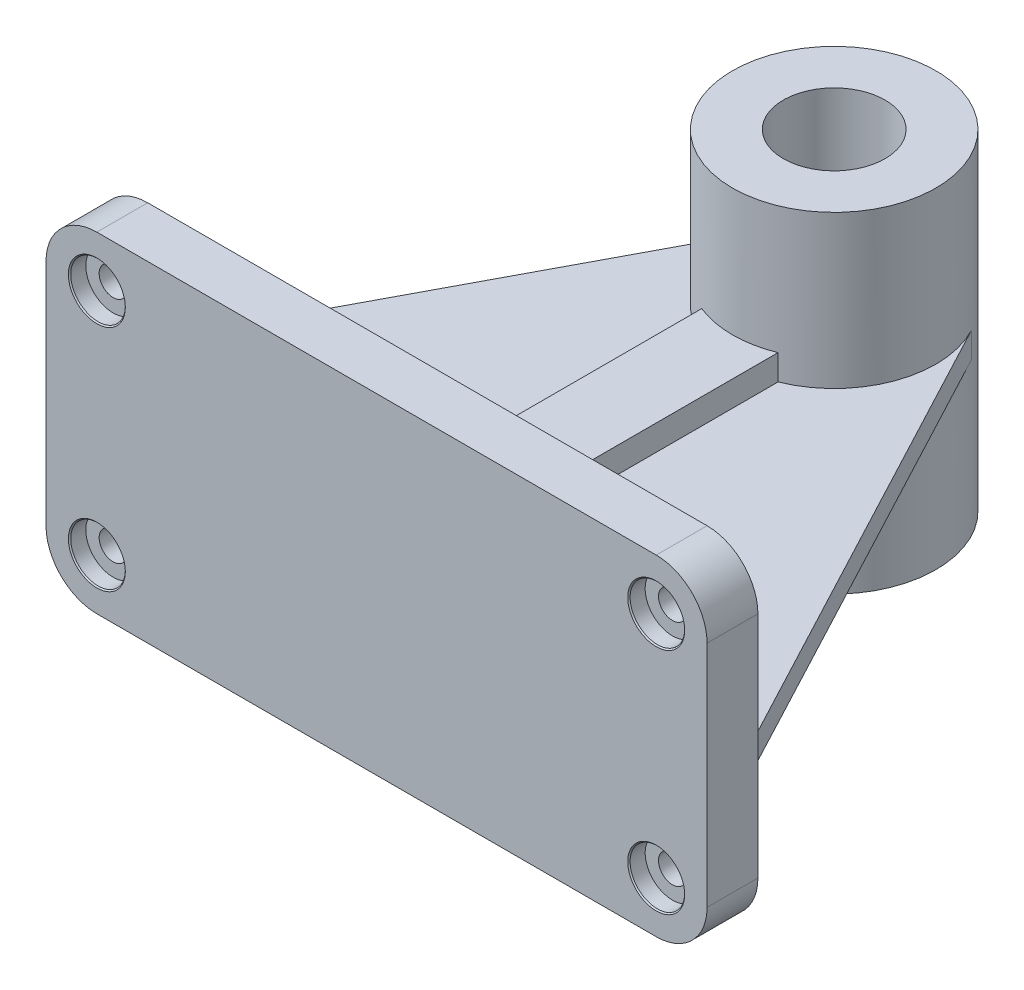
SolidWorks part; units mm, degrees
ref_plane "前视基准面" through (0, 0, 0) normal (0, 0, 1) x (1, 0, 0)
ref_plane "上视基准面" through (0, 0, 0) normal (0, 1, 0) x (1, 0, 0)
ref_plane "右视基准面" through (0, 0, 0) normal (1, 0, 0) x (0, 0, -1)
sketch "草图1" plane through (0, 0, 0) normal (0, 0, 1) x (1, 0, 0)
  line L0 (-164.2424, 0) -> (206.0606, 0) construction
  line L1 (-130, 65) -> (130, 65)
  line L2 (-130, 65) -> (-130, -65)
  line L3 (-130, -65) -> (130, -65)
  line L4 (130, 65) -> (130, -65)
  line L5 (0, 96.0606) -> (0, -170) construction
  point P4 (-164.2424, 3.0303)
  point P8 (0, 65)
  point P11 (-130, 0)
  dimension "D1" = 260
  dimension "D2" = 130
extrude "凸台-拉伸1" add sketch "草图1" along normal blind 20
hole_wizard "M10 六角头螺栓的柱形沉头孔1" positions "3D草图1" profile "草图3" counterbore size "M10" standard "ISO"
sketch3d "3D草图1"
  line L0 (130, 65, 20) -> (-130, 65, 20) construction
  line L1 (-130, 65, 20) -> (-130, -65, 20) construction
  point P0 (-110, 45, 20)
  dimension "D1" = 20
  dimension "D2" = 20
sketch "草图3" plane through (-110, 45, 20) normal (1, 0, 0) x (0, -1, 0)
  line L0 (0, 0) -> (0, 30.8047)
  line L1 (0, 30.8047) -> (5.5, 27.5)
  line L2 (5.5, 27.5) -> (5.5, 6.4)
  line L3 (5.5, 6.4) -> (10.7375, 6.4)
  line L5 (10.7375, 6.4) -> (10.7375, 0.4625)
  line L6 (10.7375, 0.4625) -> (11.2, 0)
  line L7 (11.2, 0) -> (0, 0)
  line L8 (-10.7375, 0.4625) -> (-11.2, 0) construction
  line L10 (0, 30.8047) -> (-5.5, 27.5) construction
  line L11 (0, -6.35) -> (0, 107.95) construction
  dimension "孔直径" = 11
  dimension "孔深度" = 27.5
  dimension "锥形沉头孔直径" = 21.475
  dimension "锥形沉头孔深度" = 6.4
  dimension "近端锥形沉头孔直径" = 22.4
  dimension "近端锥形沉头孔角度" = 90
  dimension "导头角度" = 118
mirror "镜向1" about plane through (0, 0, 0) normal (0, 1, 0) of "M10 六角头螺栓的柱形沉头孔1"
mirror "镜向2" about plane through (0, 0, 0) normal (1, 0, 0) of "镜向1", "M10 六角头螺栓的柱形沉头孔1"
sketch "草图4" plane through (0, 0, 0) normal (0, 1, 0) x (1, 0, 0)
  line L0 (130, 0) -> (-130, 0) construction
  circle A0 centre (0, 160) radius 40
  dimension "D1" = 80
  dimension "D2" = 160
extrude "凸台-拉伸2" add sketch "草图4" along normal mid plane 130 separate body
sketch "草图5" plane through (0, 0, 0) normal (0, 1, 0) x (1, 0, 0)
  line L0 (-15, 122.919) -> (-15, 0)
  line L1 (130, 0) -> (-130, 0) construction
  line L2 (0, 194.1484) -> (0, -59.9284) construction
  line L3 (15, 122.919) -> (15, 0)
  line L6 (-15, 0) -> (15, 0)
  circle A1 centre (0, 160) radius 40
  arc A2 (-15, 122.919) -> (15, 122.919) centre (0, 160) ccw
  dimension "D1" = 0
  dimension "D2" = 15
extrude "凸台-拉伸3" add sketch "草图5" along normal mid plane 30
sketch "草图6" plane through (0, 0, 0) normal (0, 1, 0) x (1, 0, 0)
  line L1 (130, 0) -> (35.3487, 178.7208)
  circle A0 centre (0, 160) radius 40 construction
rib "筋4" sketch "草图6" sketch "草图6" thickness 10 extrusion direction parallel to sketch draft on no parameters "D1"=10
mirror "镜向3" about plane through (0, 0, 0) normal (1, 0, 0) of "筋4"
sketch "草图7" plane through (0, 65, 0) normal (0, 1, 0) x (1, 0, 0)
  circle A0 centre (0, 160) radius 20
extrude "切除-拉伸1" cut sketch "草图7" against normal through all
fillet "圆角1" radius 20 4 edges at (-130, -65, 10) (-130, 65, 10) (130, -65, 10) (130, 65, 10)
